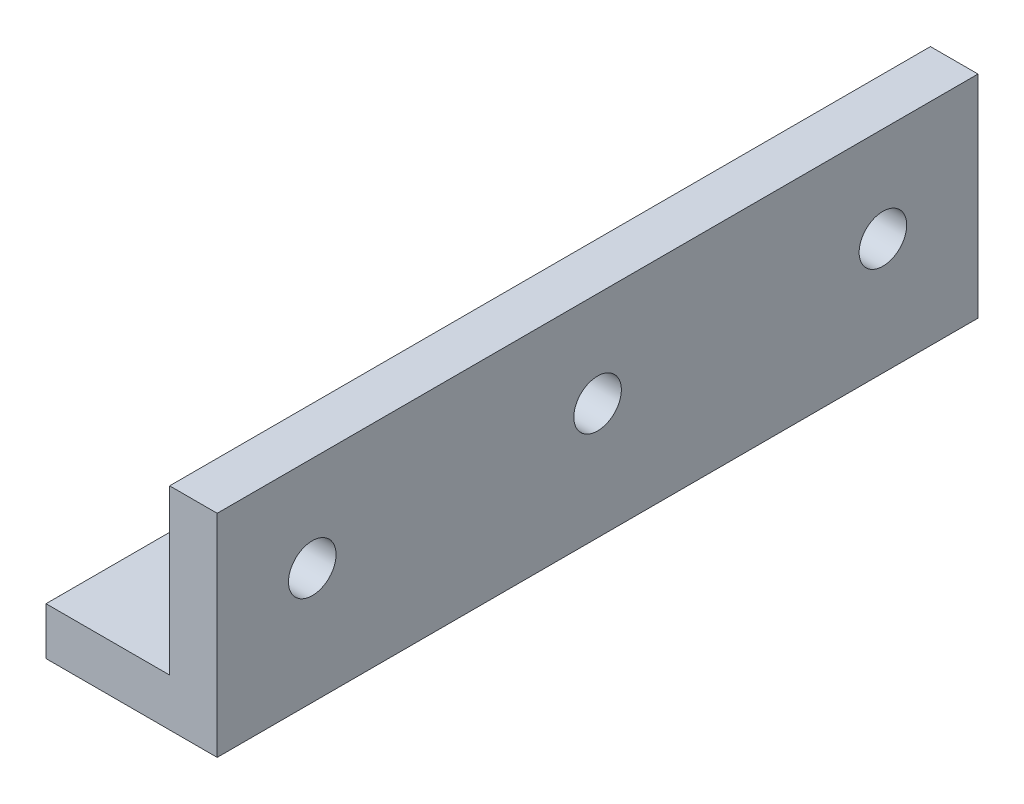
SolidWorks part; units mm, degrees
material "6061-T6 (SS)"
ref_plane "Front Plane" through (0, 0, 0) normal (0, 0, 1) x (1, 0, 0)
ref_plane "Top Plane" through (0, 0, 0) normal (0, 1, 0) x (1, 0, 0)
ref_plane "Right Plane" through (0, 0, 0) normal (1, 0, 0) x (0, 0, -1)
sketch "Sketch1" plane through (0, 0, 0) normal (0, 1, 0) x (1, 0, 0)
  line L0 (36.7349, 21.3459) -> (36.7349, -80.2541)
  line L1 (13.8749, -80.2541) -> (13.8749, 21.3459)
  line L2 (13.8749, 21.3459) -> (36.7349, 21.3459)
  line L3 (36.7349, -80.2541) -> (13.8749, -80.2541)
  dimension "D1" = 101.6
  dimension "D2" = 22.86
  dimension "D3" = 22.86
extrude "Boss-Extrude1" add sketch "Sketch1" along normal blind 6.35
sketch "Sketch2" plane through (0, 6.35, 0) normal (0, 1, 0) x (1, 0, 0)
  line L0 (36.7349, 21.3459) -> (36.7349, -80.2541)
  line L1 (36.7349, -80.2541) -> (30.3849, -80.2541)
  line L2 (13.8749, -80.2541) -> (36.7349, -80.2541) construction
  line L3 (30.3849, -80.2541) -> (30.3849, 21.3459)
  line L4 (36.7349, 21.3459) -> (13.8749, 21.3459) construction
  line L5 (30.3849, 21.3459) -> (36.7349, 21.3459)
  dimension "D1" = 6.35
extrude "Boss-Extrude2" add sketch "Sketch2" along normal blind 21.8854
sketch "Sketch3" plane through (30.3849, 0, 0) normal (-1, 0, 0) x (0, 0, 1)
  line L2 (-21.3459, 28.2354) -> (80.2541, 28.2354) construction
  line L3 (80.2541, 28.2354) -> (80.2541, 6.35) construction
  circle A0 centre (67.5541, 15.5354) radius 3.175
  circle A1 centre (29.4541, 15.5354) radius 3.175
  circle A2 centre (-8.6459, 15.5354) radius 3.175
  dimension "D6" = 6.35
  dimension "D7" = 6.35
  dimension "D8" = 6.35
  dimension "D1" = 38.1
  dimension "D2" = 38.1
  dimension "D3" = 12.7
  dimension "D4" = 12.7
  dimension "D5" = 12.7
  dimension "D9" = 12.7
extrude "Cut-Extrude1" cut sketch "Sketch3" against normal up to surface (6.35 mm away) up to face at (36.7349, 14.1177, 29.4541)
sketch "Sketch4" plane through (0, 6.35, 0) normal (0, 1, 0) x (1, 0, 0)
  line L0 (13.8749, -80.2541) -> (30.3849, -80.2541) construction
  line L1 (30.3849, 21.3459) -> (30.3849, -80.2541) construction
  circle A0 centre (24.0349, -48.5041) radius 3.175
  circle A2 centre (24.0349, -10.4041) radius 3.175
  dimension "D3" = 6.35
  dimension "D6" = 6.35
  dimension "D1" = 31.75
  dimension "D2" = 6.35
  dimension "D4" = 38.1
  dimension "D9" = 6.35
extrude "Cut-Extrude2" cut sketch "Sketch4" against normal blind 6.35
